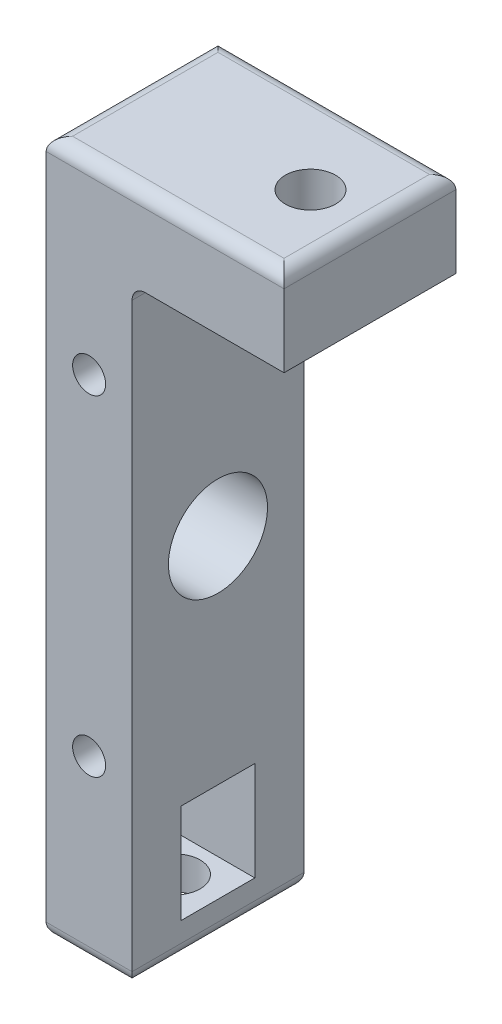
SolidWorks part; units mm, degrees
material "AISI 1020"
ref_plane "Front Plane" through (0, 0, 0) normal (0, 0, 1) x (1, 0, 0)
ref_plane "Top Plane" through (0, 0, 0) normal (0, 1, 0) x (1, 0, 0)
ref_plane "Right Plane" through (0, 0, 0) normal (1, 0, 0) x (0, 0, -1)
sketch "Sketch1" plane through (0, 0, 0) normal (0, 0, 1) x (1, 0, 0)
  line L0 (0, 0) -> (-45.72, 0)
  line L1 (-45.72, 0) -> (-45.72, -133.35)
  line L2 (-45.72, -133.35) -> (-29.21, -133.35)
  line L3 (-29.21, -133.35) -> (-29.21, -16.51)
  line L4 (-29.21, -16.51) -> (0, -16.51)
  line L5 (0, -16.51) -> (0, 0)
  dimension "D1" = 133.35
  dimension "D2" = 116.84
  dimension "D3" = 16.51
  dimension "D4" = 45.72
extrude "Boss-Extrude1" add sketch "Sketch1" along normal blind 33.02
fillet "Fillet1" radius 2.54 4 edges at (-45.72, 0, 16.51) (-22.86, 0, 0) (-22.86, 0, 33.02) (0, 0, 16.51)
sketch "Sketch4" plane through (-29.21, 0, 0) normal (1, 0, 0) x (0, 0, -1)
  line L0 (-16.51, 5.3852) -> (-16.51, -141.5607) construction
  line L1 (-58.3969, -66.548) -> (36.1502, -66.548) construction
  line L2 (0, -133.35) -> (0, -16.51) construction
  line L4 (-33.02, -133.35) -> (0, -133.35) construction
  circle A0 centre (-16.51, -66.548) radius 9.525
  dimension "D3" = 19.05
  dimension "D1" = 16.51
  dimension "D2" = 66.802
extrude "Cut-Extrude1" cut sketch "Sketch4" against normal through all
sketch "Sketch5" plane through (0, 0, 33.02) normal (0, 0, 1) x (1, 0, 0)
  line L0 (-37.465, 6.1502) -> (-37.465, -140.5278) construction
  line L1 (-67.557, -35.56) -> (-11.5573, -35.56) construction
  line L2 (-59.3368, -99.06) -> (-11.5573, -99.06) construction
  line L3 (-45.72, -2.54) -> (-45.72, -133.35) construction
  line L4 (-45.72, -133.35) -> (-29.21, -133.35) construction
  circle A0 centre (-37.465, -35.56) radius 3.175
  circle A1 centre (-37.465, -99.06) radius 3.175
  dimension "D4" = 6.35
  dimension "D5" = 6.35
  dimension "D1" = 8.255
  dimension "D2" = 34.29
  dimension "D3" = 97.79
extrude "Cut-Extrude2" cut sketch "Sketch5" against normal through all
sketch "Sketch6" plane through (-29.21, 0, 0) normal (1, 0, 0) x (0, 0, -1)
  line L0 (-16.51, 4.609) -> (-16.51, -137.7135) construction
  line L1 (-33.02, -133.35) -> (-33.02, -16.51) construction
  line L2 (-33.02, -133.35) -> (0, -133.35) construction
  line L3 (-23.5966, -107.95) -> (-9.4234, -107.95)
  line L4 (-23.5966, -107.95) -> (-23.5966, -127)
  line L5 (-23.5966, -127) -> (-9.4234, -127)
  line L6 (-9.4234, -107.95) -> (-9.4234, -127)
  line L7 (-23.5966, -107.95) -> (-9.4234, -127) construction
  line L8 (-23.5966, -127) -> (-9.4234, -107.95) construction
  point P4 (-16.51, -117.475)
  dimension "D1" = 16.51
  dimension "D2" = 6.35
  dimension "D3" = 25.4
  dimension "D4" = 14.1732
extrude "Cut-Extrude3" cut sketch "Sketch6" against normal through all
sketch "Sketch7" plane through (0, -133.35, 0) normal (0, -1, 0) x (1, 0, 0)
  line L0 (-45.72, 33.02) -> (-45.72, 0) construction
  line L1 (-52.7367, 16.51) -> (2.4569, 16.51) construction
  line L2 (-45.72, 33.02) -> (-29.21, 33.02) construction
  circle A0 centre (-37.465, 16.51) radius 4.826
  dimension "D2" = 9.652
  dimension "D1" = 16.51
  dimension "D3" = 8.255
extrude "Cut-Extrude4" cut sketch "Sketch7" against normal blind 6.35
sketch "Sketch8" plane through (0, 0, 0) normal (0, 1, 0) x (1, 0, 0)
  line L0 (-11.43, 3.1242) -> (-11.43, -36.1442) construction
  line L1 (-47.9728, -16.51) -> (7.0848, -16.51) construction
  line L2 (-45.72, 0) -> (0, 0) construction
  line L4 (-45.72, -33.02) -> (-45.72, 0) construction
  circle A0 centre (-11.43, -16.51) radius 4.826
  dimension "D3" = 9.652
  dimension "D1" = 16.51
  dimension "D2" = 34.29
extrude "Cut-Extrude5" cut sketch "Sketch8" against normal through all
fillet "Fillet2" radius 2.54 4 edges at (-37.465, -133.35, 0) (-45.72, -133.35, 16.51) (-37.465, -133.35, 33.02) (-29.21, -133.35, 16.51)
fillet "Fillet3" radius 2.54 1 edges at (-29.21, -16.51, 16.51)
